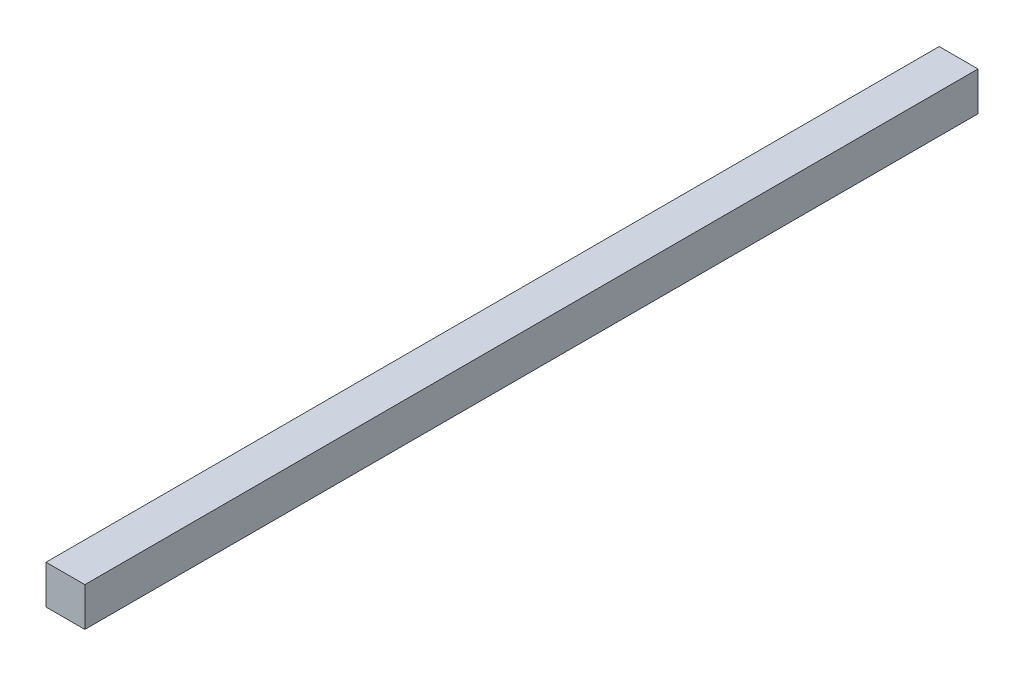
SolidWorks part; units mm, degrees
ref_plane "Front" through (0, 0, 0) normal (0, 0, 1) x (1, 0, 0)
ref_plane "Top" through (0, 0, 0) normal (0, 1, 0) x (1, 0, 0)
ref_plane "Right" through (0, 0, 0) normal (1, 0, 0) x (0, 0, -1)
sketch "Sketch1" plane through (0, 0, 0) normal (0, 0, 1) x (1, 0, 0)
  line L1 (0, 0) -> (-2.54, 0)
  line L2 (0, 0) -> (0, 2.54)
  line L3 (0, 2.54) -> (-2.54, 2.54)
  line L4 (-2.54, 0) -> (-2.54, 2.54)
  dimension "D1" = 2.54
  dimension "D2" = 2.54
extrude "Boss-Extrude1" add sketch "Sketch1" along normal blind 58.42
sketch "Sketch2" plane through (0, 0, 58.42) normal (0, 0, 1) x (1, 0, 0)
  line L0 (0, 2.54) -> (-2.54, 2.54) construction
  line L1 (0, 0) -> (0, 2.54) construction
  circle A0 centre (-1.27, 1.27) radius 0.4445
  point P0 (-1.27, 1.27)
  dimension "D3" = 0.889
  dimension "D1" = 1.27
  dimension "D2" = 1.27
